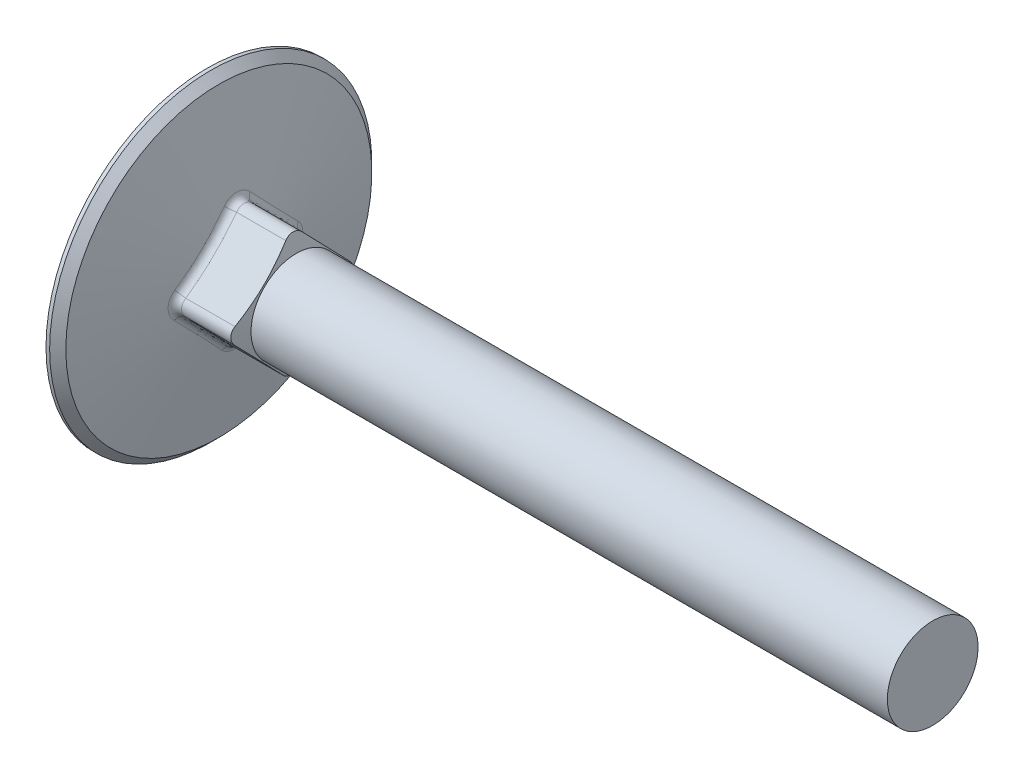
SolidWorks part; units mm, degrees
revolve "BaseBody" add sketch "BodySke"
sketch "BodySke" plane through (0, 0, 0) normal (0, 0, 1) x (1, 0, 0)
  line L0 (0, 0) -> (0, 16.9164)
  line L1 (0, 16.9164) -> (0.381, 16.9164)
  line L2 (3.429, 4.7625) -> (76.2, 4.7625)
  line L3 (76.2, 4.7625) -> (76.2, 0)
  line L4 (76.2, 0) -> (0, 0)
  line L5 (-6.35, 0) -> (82.55, 0) construction
  line L6 (3.429, -4.7625) -> (76.2, -4.7625) construction
  line L7 (0, -16.9164) -> (0.381, -16.9164) construction
  line L8 (1.2319, 16.0655) -> (3.429, 4.7625)
  line L9 (74.6125, 12.7) -> (74.6125, -3.175) construction
  line L10 (0.381, 16.9164) -> (1.2319, 16.0655)
  line L11 (38.1, 12.7) -> (38.1, -3.175) construction
  dimension "D1" = 0.381
  dimension "Diameter" = 9.525
  dimension "D2" = 45
  dimension "Length" = 76.2
  dimension "Head_ht" = 3.429
  dimension "Head_dia" = 33.8328
  dimension "Head_ang" = 11
  dimension "Advance" = 1.5875
  dimension "Thread_nom" = 38.1
cosmetic thread "ThreadCosmetic" [suppressed]
revolve "NeckChamfer" cut sketch "Sketch3" angle 360 about L4
sketch "Sketch3" plane through (0, 0, 0) normal (0, 0, 1) x (1, 0, 0)
  line L0 (2.713, 29.6164) -> (9.3726, 4.7625)
  line L1 (9.3726, 4.7625) -> (9.6266, 4.7625)
  line L2 (9.6266, 4.7625) -> (9.6266, 29.6164)
  line L3 (9.6266, 29.6164) -> (2.713, 29.6164)
  line L4 (0, 0) -> (22.225, 0) construction
  line L9 (0.381, 16.9164) -> (0, 16.9164) construction
  dimension "D1" = 12.7
  dimension "D2" = 4.7625
  dimension "D3" = 105
  dimension "D4" = 0.254
  dimension "D5" = 9.3726
ref_plane "Plane1" through (0, 0, 0) normal (0, 0, 1) x (1, 0, 0)
ref_plane "Plane2" through (0, 0, 0) normal (0, 1, 0) x (1, 0, 0)
ref_plane "Plane3" through (0, 0, 0) normal (1, 0, 0) x (0, 0, -1)
sketch "Sketch2" plane through (0, 0, 0) normal (1, 0, 0) x (0, 0.6947, -0.7193)
  line L1 (3.7084, -4.9022) -> (-3.7084, -4.9022)
  line L2 (4.9022, -3.7084) -> (4.9022, 3.7084)
  line L3 (3.7084, 4.9022) -> (-3.7084, 4.9022)
  line L4 (-4.9022, -3.7084) -> (-4.9022, 3.7084)
  arc A0 (3.7084, 4.9022) -> (4.9022, 3.7084) centre (3.7084, 3.7084) cw
  arc A1 (3.7084, -4.9022) -> (4.9022, -3.7084) centre (3.7084, -3.7084) ccw
  arc A2 (-4.9022, -3.7084) -> (-3.7084, -4.9022) centre (-3.7084, -3.7084) ccw
  arc A3 (-3.7084, 4.9022) -> (-4.9022, 3.7084) centre (-3.7084, 3.7084) ccw
  dimension "Neck_corner_radius" = 1.1938
  dimension "Neck_width" = 9.8044
  dimension "D1" = 4.9022
  dimension "D2" = 9.8044
  dimension "D3" = 4.9022
extrude "Neck" add sketch "Sketch2" along normal blind 9.3726
fillet "HeadFillet" radius 0.7874 8 edges at (3.283, 1.5902, -5.2793) (3.1045, 0.0247, -6.4318) (3.283, -5.2793, -1.5902) (3.1045, -6.4318, -0.0247) (3.283, -1.5902, 5.2793) (3.1045, -0.0247, 6.4318) (3.283, 5.2793, 1.5902) (3.1045, 6.4318, 0.0247)
sketch "ThdSchSke" plane through (0, 0, 0) normal (0, 0, 1) x (1, 0, 0)
  line L0 (38.1, -3.8163) -> (37.4375, -4.7625)
  line L1 (38.1, -3.8163) -> (38.7625, -4.7625)
  line L2 (38.7625, -4.7625) -> (38.7625, -5.9531)
  line L3 (-3.175, 0) -> (5.1513, 0) construction
  line L5 (38.7625, -5.9531) -> (37.4375, -5.9531)
  line L6 (37.4375, -5.9531) -> (37.4375, -4.7625)
  line L7 (0, 16.9164) -> (0, -16.9164) construction
  dimension "Thread_minor" = 7.6327
  dimension "Diameter" = 9.525
  dimension "Start" = 38.1
revolve "ThreadSchematic" [suppressed] cut sketch "ThdSchSke" angle 360 about L3
pattern_linear "ThdSchPat" [suppressed]
equation "\"D1@Sketch2\" = \"Neck_width@Sketch2\"/2"
equation "\"D2@Sketch2\" = \"Neck_width@Sketch2\""
equation "\"D3@Sketch2\" = \"D2@Sketch2\"/2"
equation "\"D2@Sketch3\" = \"Diameter@BodySke\"/2"
equation "\"D5@Sketch3\" = \"Neck_ht@Neck\""
equation "\"Thread_length@ThreadCosmetic\" = ((sgn( (\"Length@BodySke\" - \"Advance@BodySke\" * 1.5 - \"Neck_ht@Neck\" ) - \"Thread_nom@BodySke\" )-1)*( (\"Length@BodySke\" - \"Advance@BodySke\" * 1.5 - \"Neck_ht@Neck\" ) - \"Thread_nom@BodySke\" ))/-2+ \"Thread_nom@BodySke\""
equation "\"Thread_minor@ThdSchSke\" = \"Thread_minor@ThreadCosmetic\""
equation "\"Diameter@ThdSchSke\" = \"Diameter@BodySke\""
equation "\"Overcut@ThdSchSke\" = \"Diameter@BodySke\" * 1.25"
equation "\"Start@ThdSchSke\" = 0.000001 + \"Length@BodySke\" - \"Thread_length@ThreadCosmetic\"  '---Countersunk---"
equation "\"Num_threads@ThdSchPat\" = int( \"Thread_length@ThreadCosmetic\" / \"Advance@BodySke\" + 0.999 )  + 1"
equation "\"Advance@ThdSchPat\" = \"Thread_length@ThreadCosmetic\" /  (\"Num_threads@ThdSchPat\" - 1) 'relax it"
